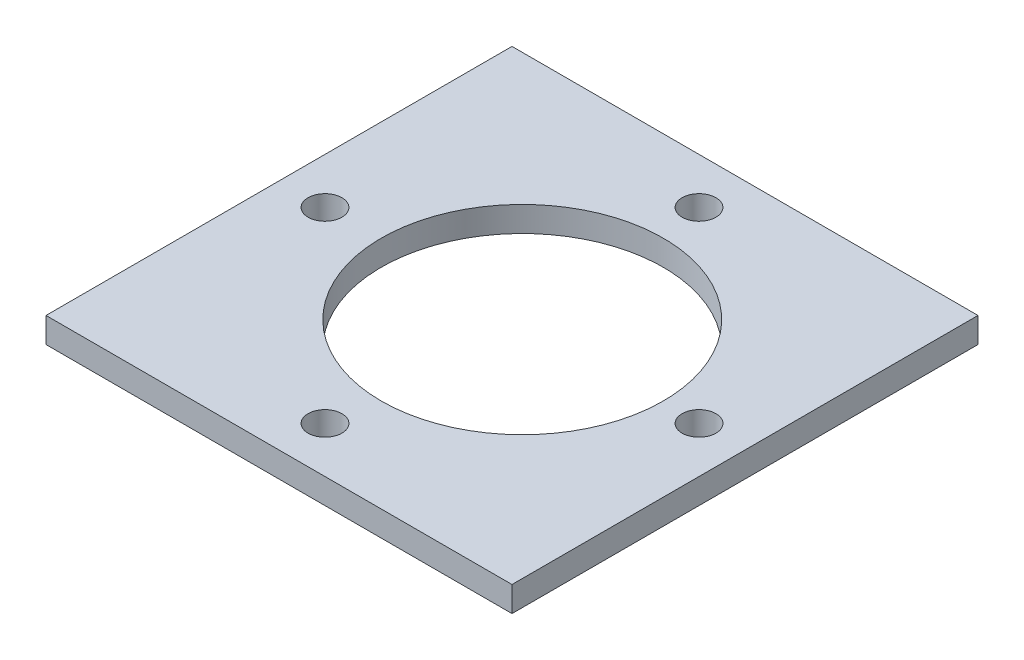
SolidWorks part; units mm, degrees
material "6061-T6 (SS)"
ref_plane "Front Plane" through (0, 0, 0) normal (0, 0, 1) x (1, 0, 0)
ref_plane "Top Plane" through (0, 0, 0) normal (0, 1, 0) x (1, 0, 0)
ref_plane "Right Plane" through (0, 0, 0) normal (1, 0, 0) x (0, 0, -1)
sketch "Sketch1" plane through (0, 0, 0) normal (0, 1, 0) x (1, 0, 0)
  line L1 (0, 0) -> (82.6, 0)
  line L2 (0, 0) -> (0, 82.6)
  line L3 (0, 82.6) -> (82.6, 82.6)
  line L4 (82.6, 0) -> (82.6, 82.6)
  dimension "D1" = 82.6
  dimension "D2" = 82.6
extrude "Boss-Extrude1" add sketch "Sketch1" along normal blind 4.47
sketch "Sketch5" plane through (0, 4.47, 0) normal (0, 1, 0) x (1, 0, 0)
  circle A0 centre (42.8419, 41.5753) radius 25
  dimension "D1" = 50
extrude "Cut-Extrude2" cut sketch "Sketch5" against normal through all
sketch "Sketch7" plane through (0, 4.47, 0) normal (0, 1, 0) x (1, 0, 0)
  line L0 (82.6, 82.6) -> (0, 82.6) construction
  line L1 (82.6, 0) -> (82.6, 82.6) construction
  line L2 (0, 82.6) -> (0, 0) construction
  line L3 (0, 0) -> (82.6, 0) construction
  circle A0 centre (8.15, 41.3) radius 3
  circle A1 centre (41.3, 74.45) radius 3
  circle A2 centre (74.45, 41.3) radius 3
  circle A3 centre (41.3, 8.15) radius 3
  dimension "D1" = 6
  dimension "D2" = 41.3
  dimension "D3" = 8.15
  dimension "D4" = 8.15
  dimension "D5" = 41.3
  dimension "D6" = 6
  dimension "D7" = 8.15
  dimension "D8" = 6
  dimension "D9" = 41.3
  dimension "D10" = 6
  dimension "D11" = 41.3
  dimension "D12" = 8.15
extrude "Cut-Extrude3" cut sketch "Sketch7" against normal through all
